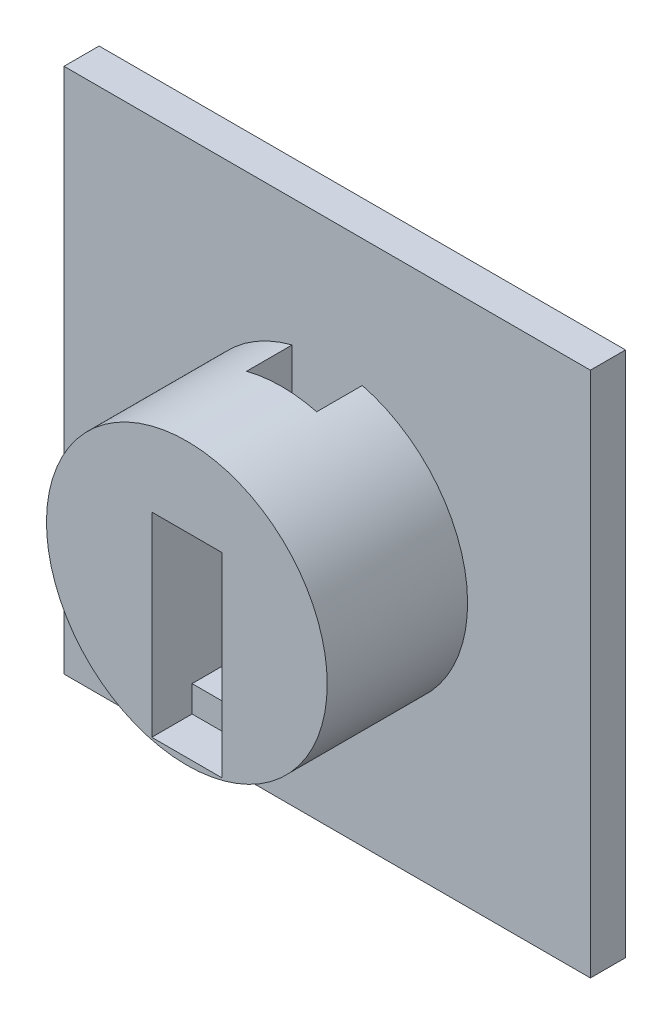
SolidWorks part; units mm, degrees
ref_plane "Alzado" through (0, 0, 0) normal (1, 0, 0) x (0, 1, 0)
ref_plane "Planta" through (0, 0, 0) normal (0, 0, 1) x (0, 1, 0)
ref_plane "Vista lateral" through (0, 0, 0) normal (0, 1, 0) x (-1, 0, 0)
sketch "Croquis1" plane through (0, 0, 0) normal (0, 0, 1) x (0, 1, 0)
  line L1 (75, 75) -> (-75, 75)
  line L2 (75, 75) -> (75, -75)
  line L3 (75, -75) -> (-75, -75)
  line L4 (-75, 75) -> (-75, -75)
  line L5 (75, 75) -> (-75, -75) construction
  line L6 (75, -75) -> (-75, 75) construction
  point P0 (0, 0)
extrude "Saliente-Extruir1" add sketch "Croquis1" along normal blind 10
sketch "Croquis2" plane through (0, 0, 10) normal (0, 0, 1) x (1, 0, 0)
  circle A0 centre (0, 0) radius 40
extrude "Saliente-Extruir2" add sketch "Croquis2" along normal blind 40
sketch "Croquis3" plane through (0, 0, 50) normal (0, 0, 1) x (1, 0, 0)
  line L1 (0, 10) -> (-10, 10)
  line L2 (-10, 10) -> (-10, -30.6)
  line L3 (-10, -30.6) -> (10, -30.6)
  line L4 (10, -30.6) -> (10, 10)
  line L5 (10, 10) -> (0, 10)
extrude "Cortar-Extruir1" cut sketch "Croquis3" against normal blind 41
sketch "Croquis4" plane through (0, 0, 50) normal (0, 0, 1) x (1, 0, 0)
  line L0 (-10, -30.6) -> (-10, -38.1)
  line L1 (-10, -38.1) -> (10, -38.1)
  line L2 (10, -38.1) -> (10, -30.6)
  line L3 (-10, -30.6) -> (10, -30.6)
  line L4 (-10, 10) -> (-10, 17.5)
  line L5 (10, 10) -> (-10, 10) construction
  line L6 (-10, 17.5) -> (10, 17.5)
  line L7 (10, 17.5) -> (10, 10)
  line L8 (10, 10) -> (-10, 10)
extrude "Cortar-Extruir2" cut sketch "Croquis4" against normal blind 11.5
sketch "Croquis5" plane through (0, 0, 50) normal (0, 0, 1) x (1, 0, 0)
  line L8 (-10, 10) -> (10, 10)
  line L9 (-10, 10) -> (-10, 44.5312)
  line L10 (-10, 44.5312) -> (10, 44.5312)
  line L11 (10, 10) -> (10, 44.5312)
extrude "Cortar-Extruir3" cut sketch "Croquis5" against normal blind 13 from offset 27
